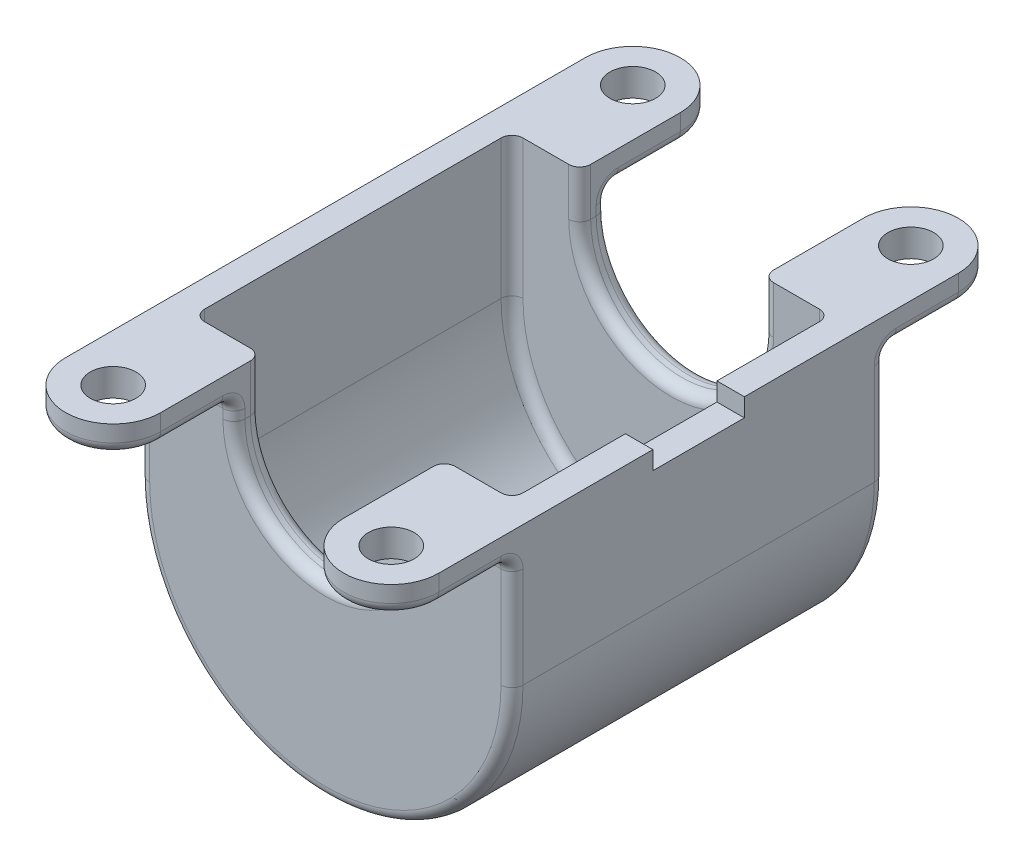
SolidWorks part; units mm, degrees
ref_plane "Front" through (0, 0, 0) normal (0, 0, 1) x (1, 0, 0)
ref_plane "Top" through (0, 0, 0) normal (0, 1, 0) x (1, 0, 0)
ref_plane "Right" through (0, 0, 0) normal (1, 0, 0) x (0, 0, -1)
sketch "Sketch1" plane through (0, 0, 0) normal (0, 0, 1) x (1, 0, 0)
  line L0 (-51, 0) -> (-51, 38)
  line L1 (-51, 38) -> (-25, 38)
  line L2 (-25, 38) -> (-25, 25)
  line L3 (51, 0) -> (51, 38)
  line L4 (51, 38) -> (25, 38)
  line L5 (25, 38) -> (25, 25)
  arc A0 (51, 0) -> (-51, 0) centre (0, 0) cw
  arc A1 (25, 25) -> (-25, 25) centre (0, 25) cw
  dimension "D1" = 51
  dimension "D2" = 25
  dimension "D3" = 38
extrude "Base-Extrude" add sketch "Sketch1" along normal mid plane 102
shell "Shell1" thickness 7.5
sketch "Sketch2" plane through (0, 38, 0) normal (0, 1, 0) x (-1, 0, 0)
  line L0 (51, 51) -> (51, 71)
  line L1 (51, 51) -> (25, 51)
  line L2 (25, 51) -> (25, 71)
  arc A0 (25, 71) -> (51, 71) centre (38, 71) cw
  dimension "D1" = 20
extrude "Boss-Extrude1" add sketch "Sketch2" against normal blind 7.5
sketch "Sketch3" plane through (0, 38, 0) normal (0, 1, 0) x (-1, 0, 0)
  circle A0 centre (38, 71) radius 6.25
  dimension "D1" = 12.5
extrude "Cut-Extrude1" cut sketch "Sketch3" against normal through all
mirror "Mirror1" about plane through (0, 0, 0) normal (1, 0, 0) of "Cut-Extrude1", "Boss-Extrude1"
mirror "Mirror2" about plane through (0, 0, 0) normal (0, 0, 1) of "Mirror1", "Boss-Extrude1", "Cut-Extrude1"
sketch "Sketch4" plane through (51, 0, 0) normal (1, 0, 0) x (0, 0, -1)
  line L0 (-71, 38) -> (71, 38) construction
  line L1 (-12.5, 38) -> (12.5, 38)
  line L2 (-12.5, 38) -> (-12.5, 33)
  line L3 (-12.5, 33) -> (12.5, 33)
  line L4 (12.5, 38) -> (12.5, 33)
  line L5 (0, 0) -> (0, 38) construction
  dimension "D1" = 5
  dimension "D2" = 25
extrude "Cut-Extrude2" cut sketch "Sketch4" against normal up to next
fillet "Fillet1" radius 3 8 edges at (-38, 30.5, -51) (38, 30.5, 51)
fillet "Fillet2" radius 3 44 edges at (-38, 30.5, -84) (-25, 30.5, -62.5) (0, -51, -51) (-51, 30.5, -62.5) (-51, 13.75, -51) (51, 30.5, 62.5) (25, 26.25, 51) (-51, 29.6213, -51.8787) (-25, 29.6213, -51.8787) (51, 29.6213, -51.8787) (25, 29.6213, -51.8787) (51, 29.6213, 51.8787) (25, 29.6213, 51.8787) (-51, 29.6213, 51.8787) (-25, 29.6213, 51.8787) (0, 0, 51) (0, -43.5, -43.5) (43.5, 19, -43.5) (25, 31.5, -43.5) (0, 0, -43.5) (-25, 31.5, -43.5) (-43.5, 19, -43.5) (0, -43.5, 43.5) (43.5, 19, 43.5) (25, 31.5, 43.5) (0, 0, 43.5) (-25, 31.5, 43.5) (-43.5, 19, 43.5) (0, -51, 51) (-38, 30.5, 84) (38, 30.5, 84) (25, 30.5, 62.5) (51, 13.75, 51) (38, 30.5, -84) (-25, 26.25, -51) (0, 0, -51)
